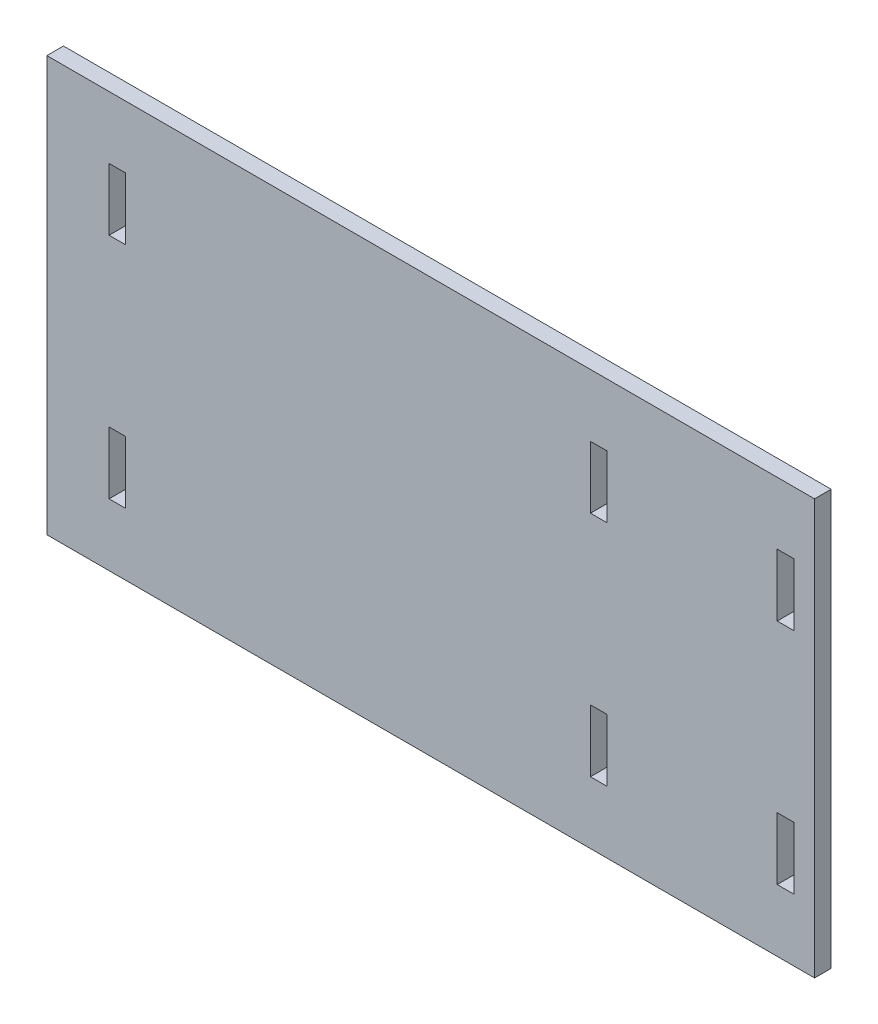
SolidWorks part; units mm, degrees
ref_plane "Front Plane" through (0, 0, 0) normal (0, 0, 1) x (1, 0, 0)
ref_plane "Top Plane" through (0, 0, 0) normal (0, 1, 0) x (1, 0, 0)
ref_plane "Right Plane" through (0, 0, 0) normal (1, 0, 0) x (0, 0, -1)
sketch "Sketch1" plane through (0, 0, 0) normal (0, 0, 1) x (1, 0, 0)
  line L0 (0, 66.0849) -> (0, -70.4198) construction
  line L1 (-75, -50) -> (75, -50)
  line L3 (-75, 50) -> (75, 50)
  line L5 (-75, -50) -> (75, 50) construction
  line L6 (-75, 50) -> (75, -50) construction
  line L7 (56, 35) -> (60, 35)
  line L8 (56, 35) -> (56, 20)
  line L9 (56, 20) -> (60, 20)
  line L10 (60, 35) -> (60, 20)
  line L11 (-103.5149, 0) -> (102.2922, 0) construction
  line L12 (56, -20) -> (60, -20)
  line L13 (56, -35) -> (56, -20)
  line L14 (60, -35) -> (60, -20)
  line L15 (56, -35) -> (60, -35)
  line L16 (-56, 35) -> (-60, 35)
  line L17 (-56, 35) -> (-56, 20)
  line L18 (-60, 35) -> (-60, 20)
  line L19 (-56, 20) -> (-60, 20)
  line L20 (-56, -20) -> (-60, -20)
  line L21 (-56, -35) -> (-56, -20)
  line L22 (-60, -35) -> (-60, -20)
  line L23 (-56, -35) -> (-60, -35)
  line L27 (75, 50) -> (110, 50)
  line L36 (110, 50) -> (110, -50)
  line L37 (110, -50) -> (75, -50)
  line L38 (-75, -50) -> (-75, 50)
  line L39 (101, 35) -> (105, 35)
  line L40 (101, 35) -> (101, 20)
  line L41 (101, 20) -> (105, 20)
  line L42 (105, 35) -> (105, 20)
  line L43 (101, -20) -> (105, -20)
  line L44 (101, -20) -> (101, -35)
  line L45 (101, -35) -> (105, -35)
  line L46 (105, -20) -> (105, -35)
  point P0 (0, 0)
  dimension "D1" = 100
  dimension "D2" = 150
  dimension "D3" = 5
  dimension "D4" = 15
  dimension "D5" = 4
  dimension "D6" = 15
  dimension "D8" = 5
  dimension "D9" = 35
extrude "Boss-Extrude1" add sketch "Sketch1" along normal blind 4
